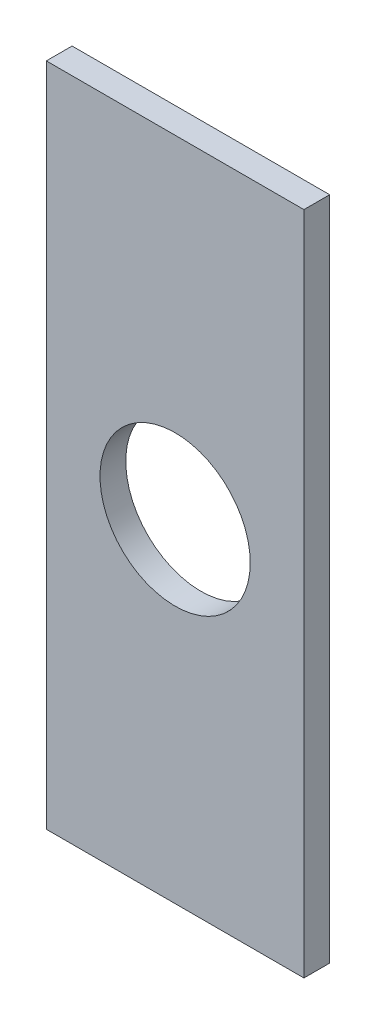
SolidWorks part; units mm, degrees
material "Q355"
ref_plane "前视基准面" through (0, 0, 0) normal (0, 0, 1) x (1, 0, 0)
ref_plane "上视基准面" through (0, 0, 0) normal (0, 1, 0) x (1, 0, 0)
ref_plane "右视基准面" through (0, 0, 0) normal (1, 0, 0) x (0, 0, -1)
sketch "草图1" plane through (0, 0, 0) normal (0, 0, 1) x (1, 0, 0)
  line L1 (-60, 155) -> (60, 155)
  line L2 (-60, 155) -> (-60, -155)
  line L3 (-60, -155) -> (60, -155)
  line L4 (60, 155) -> (60, -155)
  circle A0 centre (0, 0) radius 35
  point P0 (0, 0)
  dimension "D3" = 70
  dimension "D4" = 155
  dimension "D5" = 60
  dimension "D1" = 120
  dimension "D2" = 310
extrude "凸台-拉伸1" add sketch "草图1" along normal blind 12
